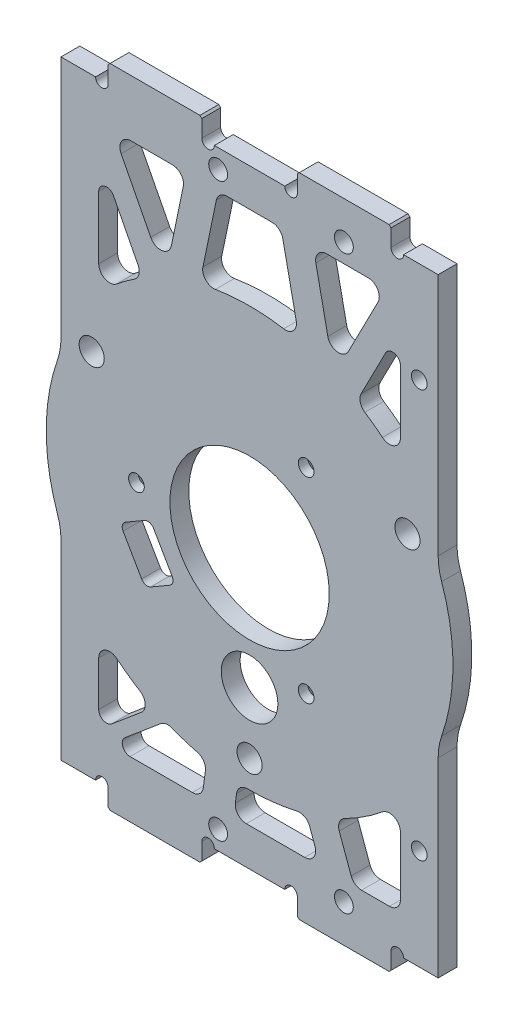
SolidWorks part; units mm, degrees
material "Thornel Mat VMA"
ref_plane "前视基准面" through (0, 0, 0) normal (0, 0, 1) x (1, 0, 0)
ref_plane "上视基准面" through (0, 0, 0) normal (0, 1, 0) x (1, 0, 0)
ref_plane "右视基准面" through (0, 0, 0) normal (1, 0, 0) x (0, 0, -1)
sketch "草图1" plane through (0, 0, 0) normal (0, 0, 1) x (1, 0, 0)
  line L1 (-30, 44.25) -> (30, 44.25)
  line L2 (-30, 44.25) -> (-30, -44.25)
  line L3 (-30, -44.25) -> (30, -44.25)
  line L4 (30, 44.25) -> (30, -44.25)
  line L5 (0, -44.25) -> (0, 44.25) construction
  line L6 (-30, 0) -> (30, 0) construction
  circle A0 centre (0, 0) radius 29 construction
  circle A1 centre (25.1147, 14.5) radius 2
  circle A2 centre (0, -29) radius 2
  circle A3 centre (-25.1147, 14.5) radius 2
  point P0 (0, 0)
  point P17 (0, 0)
  dimension "D1" = 58
  dimension "D4" = 4
  dimension "D3" = 44.25
  dimension "D2" = 60
  dimension "D5" = 3
extrude "凸台-拉伸1" add sketch "草图1" along normal blind 3
sketch "草图2" plane through (0, 0, 3) normal (0, 0, 1) x (1, 0, 0)
  circle A0 centre (0, 0) radius 12.675
  dimension "D1" = 25.35
extrude "切除-拉伸1" cut sketch "草图2" against normal blind 3
sketch "草图4" plane through (0, 0, 3) normal (0, 0, 1) x (1, 0, 0)
  line L0 (-12.7296, 10.3517) -> (-15.3296, 5.8483) construction
  line L1 (-12.7296, 10.3517) -> (-15.3296, 5.8483)
  line L2 (-16.0126, 5.6653) -> (-19.1303, 7.4653) construction
  line L3 (-16.0126, 5.6653) -> (-19.1303, 7.4653)
  line L4 (-19.3133, 8.1483) -> (-16.7133, 12.6517) construction
  line L5 (-19.3133, 8.1483) -> (-16.7133, 12.6517)
  circle A0 centre (-16.671, -9.625) radius 4 construction
  circle A1 centre (-16.671, -9.625) radius 4
sketch "草图5" plane through (0, 0, 3) normal (0, 0, 1) x (1, 0, 0)
  line L0 (-12.7296, 10.3517) -> (-15.3296, 5.8483) construction
  line L1 (-15.5796, 5.4153) -> (-12.0796, 11.4775)
  line L2 (-12.0796, 11.4775) -> (-16.0633, 13.7775)
  line L3 (-16.0633, 13.7775) -> (-19.5633, 7.7153)
  line L4 (-19.5633, 7.7153) -> (-15.5796, 5.4153)
  line L5 (-16.0126, 5.6653) -> (-19.1303, 7.4653) construction
  line L6 (-19.3133, 8.1483) -> (-16.7133, 12.6517) construction
  line L7 (-15.3966, 4.7323) -> (-11.3966, 11.6605)
  line L8 (-11.3966, 11.6605) -> (-16.2463, 14.4605)
  line L9 (-16.2463, 14.4605) -> (-20.2463, 7.5323)
  line L10 (-20.2463, 7.5323) -> (-15.3966, 4.7323)
  line L11 (12.4796, 10.7847) -> (15.9796, 4.7225)
  line L12 (15.9796, 4.7225) -> (19.9633, 7.0225)
  line L13 (19.9633, 7.0225) -> (16.4633, 13.0847)
  line L14 (16.4633, 13.0847) -> (12.4796, 10.7847)
  line L15 (11.7966, 10.9677) -> (15.7966, 4.0395)
  line L16 (15.7966, 4.0395) -> (20.6463, 6.8395)
  line L17 (20.6463, 6.8395) -> (16.6463, 13.7677)
  line L18 (16.6463, 13.7677) -> (11.7966, 10.9677)
  line L19 (3.1, -16.2) -> (-3.9, -16.2) construction
  line L20 (-3.9, -16.2) -> (-3.9, -20.8) construction
  line L21 (-3.9, -20.8) -> (3.1, -20.8) construction
  line L22 (3.1, -20.8) -> (3.1, -16.2) construction
  line L23 (3.6, -15.7) -> (-4.4, -15.7) construction
  line L24 (-4.4, -15.7) -> (-4.4, -21.3) construction
  line L25 (-4.4, -21.3) -> (3.6, -21.3) construction
  line L26 (3.6, -21.3) -> (3.6, -15.7) construction
  line L27 (-11.7966, -10.9677) -> (-15.7966, -4.0395)
  line L28 (-15.7966, -4.0395) -> (-20.6463, -6.8395)
  line L29 (-20.6463, -6.8395) -> (-16.6463, -13.7677)
  line L30 (-16.6463, -13.7677) -> (-11.7966, -10.9677)
  circle A0 centre (-16.671, -9.625) radius 4.5 construction
  circle A1 centre (0, 19.25) radius 4.5
  circle A2 centre (16.671, -9.625) radius 4.5
  circle A3 centre (0, -19.25) radius 4.5
  point P39 (0, 0)
  point P48 (0, 0)
  dimension "D1" = 9
  dimension "D2" = 7
  dimension "D3" = 0.5
  dimension "D6" = 60
  dimension "D4" = 3
  dimension "D5" = 2
extrude "切除-拉伸2" cut sketch "草图5" against normal blind 10 contours A0 | L29 L30 L27 L28 | A3 | L1 L2 L3 L4
sketch "草图6" plane through (0, 0, 3) normal (0, 0, 1) x (1, 0, 0)
  line L4 (30, -44.25) -> (30, 44.25)
  line L5 (30, 44.25) -> (-30, 44.25)
  line L6 (-30, 44.25) -> (-30, -44.25)
  line L7 (-30, -44.25) -> (30, -44.25)
  line L8 (30, -12.1046) -> (30, 12.1046)
  line L9 (30, 44.25) -> (-30, 44.25)
  line L10 (-30, 12.1046) -> (-30, -12.1046)
  arc A0 (-30, 12.1046) -> (-30, -12.1046) centre (0, 0) ccw
  arc A1 (30, -12.1046) -> (30, 12.1046) centre (0, 0) ccw
  line M10 (-30, 44.25) -> (-30, -44.25)
  dimension "D1" = 64.7
  dimension "D2" = 0
extrude "凸台-拉伸2" add sketch "草图6" against normal up to surface (3 mm away) contours A0 M10 | L8 A1 up to face at (-16.2215, -8.9036, 0)
sketch "草图7" plane through (0, 0, 0) normal (0, 0, -1) x (-1, 0, 0)
  line L0 (-30, 12.1046) -> (-30, 44.25) construction
  line L1 (30, 44.25) -> (-30, 44.25)
  line L2 (30, 44.25) -> (30, 52.65)
  line L3 (30, 52.65) -> (-30, 52.65)
  line L4 (-30, 44.25) -> (-30, 52.65)
  dimension "D1" = 8.4
extrude "凸台-拉伸3" add sketch "草图7" against normal up to surface (3 mm away) up to face at (-16.2215, -8.9036, 3)
sketch "草图8" plane through (0, 0, 0) normal (0, 0, -1) x (-1, 0, 0)
  line L0 (24, 12.1046) -> (24, 46.65)
  line L1 (24, 46.65) -> (-24, 46.65)
  line L2 (-24, 46.65) -> (-24, 12.1046)
  line L3 (-24, -12.1046) -> (-24, -38.25)
  line L4 (-24, -38.25) -> (24, -38.25)
  line L5 (24, -38.25) -> (24, -12.1046)
  line L6 (-30, -12.1046) -> (-30, -44.25)
  line L7 (-30, -44.25) -> (30, -44.25)
  line L8 (30, -44.25) -> (30, -12.1046)
  line L9 (30, 12.1046) -> (30, 52.65)
  line L10 (30, 52.65) -> (-30, 52.65)
  line L11 (-30, 52.65) -> (-30, 12.1046)
  line L12 (-30, -12.1046) -> (-30, -44.25)
  line L13 (-30, -44.25) -> (30, -44.25)
  line L14 (30, -44.25) -> (30, -12.1046)
  line L15 (30, 12.1046) -> (30, 52.65)
  line L16 (30, 52.65) -> (-30, 52.65)
  line L17 (-30, 52.65) -> (-30, 12.1046)
  line L18 (0, 0) -> (-13.9219, -38.25)
  line L19 (0, 0) -> (5.0357, -38.25)
  line L20 (1.1451, 10.4556) -> (11.5962, -68.9286)
  line L21 (1.1451, 10.4556) -> (-21.9953, -53.1222)
  line L22 (-1.1451, -10.4556) -> (5.3791, -60.0118)
  line L23 (-1.1451, -10.4556) -> (-15.2052, -49.0855)
  line L24 (1.1451, 10.4556) -> (-16.2711, -37.3949) construction
  line L25 (1.1451, 10.4556) -> (7.745, -39.6758) construction
  line L26 (0, 0) -> (0, -73.8949) construction
  line L27 (0, 0) -> (77.4058, 0) construction
  line L28 (24, 46.65) -> (15.6774, 30.4729) construction
  line L29 (-24, 46.65) -> (-15.4503, 30.0316) construction
  line L30 (-25.7784, 45.735) -> (-17.2288, 29.1167) construction
  line L31 (25.7784, 45.735) -> (17.4558, 29.558) construction
  line L32 (-1.1451, -10.4556) -> (-11.5726, -39.1051) construction
  line L33 (-1.1451, -10.4556) -> (2.7878, -40.3285) construction
  line L34 (21.8007, 46.747) -> (13.457, 30.5288)
  line L35 (-25.7784, 45.735) -> (-17.0078, 28.6872)
  line L36 (25.7784, 45.735) -> (17.0078, 28.6872)
  line L37 (-22.3053, 47.7277) -> (-13.457, 30.5288)
  line L38 (-22.2216, 47.565) -> (-13.6719, 30.9466) construction
  line L39 (22.2216, 47.565) -> (13.8989, 31.3879) construction
  line L40 (24, 46.65) -> (15.2569, 29.6555)
  line L41 (-8.0641, 46.65) -> (-11.2329, 31.4013) construction
  line L42 (-24, 46.65) -> (0, 0)
  line L43 (-10.1068, 46.65) -> (-13.457, 30.5288)
  line L44 (-5, 46.65) -> (-8.2957, 30.791)
  line L45 (-9.8954, 47.6673) -> (-13.1911, 31.8083) construction
  line L46 (-5, 46.65) -> (-8.2957, 30.791) construction
  line L47 (10.1068, 46.65) -> (13.457, 30.5288)
  line L48 (5, 46.65) -> (8.2957, 30.791)
  line L49 (-7.9372, 47.2604) -> (-11.2329, 31.4013) construction
  line L50 (0, 0) -> (5.2664, -40.0022) construction
  line L51 (14.3136, -30.1221) -> (24, -38.25) construction
  line L52 (13.3048, -30.5811) -> (23.3572, -39.016)
  line L53 (15.2918, -29.6375) -> (24.6428, -37.484)
  line L54 (9.1091, -27.0605) -> (23.3572, -39.016) construction
  line L55 (10.3947, -25.5284) -> (24.6428, -37.484) construction
  line L56 (9.7519, -26.2944) -> (24, -38.25) construction
  circle A0 centre (0, 0) radius 33.35
  arc A3 (30, -12.1046) -> (30, 12.1046) centre (0, 0) ccw
  arc A4 (-30, 12.1046) -> (-30, -12.1046) centre (0, 0) ccw
  dimension "D1" = 66.7
  dimension "D3" = 20
  dimension "D4" = 7.5
  dimension "D5" = 2.5
  dimension "D6" = 2.5
  dimension "D7" = 6
  dimension "D8" = 2
  dimension "D10" = 2
  dimension "D12" = 10
  dimension "D13" = 1
  dimension "D15" = 40
  dimension "D2" = 0
  dimension "D9" = 2
  dimension "D11" = 3
  dimension "D14" = 1
extrude "切除-拉伸3" cut sketch "草图8" against normal blind 10 contours A0 L35 L2 | L43 L1 L37 | A0 L48 L1 L44 | L1 L47 L34 | A0 L0 L36 | A0 L23 L4 L22 | A0 L3 L4 L21 | A0 L20 L4 L52 | A0 L53 L5
sketch "草图9" plane through (0, 0, 0) normal (0, 0, -1) x (-1, 0, 0)
  line L0 (5, 49.65) -> (-15, 49.65) construction
  line L1 (30, 52.65) -> (-30, 52.65) construction
  line L2 (0, 52.65) -> (0, -44.25) construction
  line L3 (-30, 12.1046) -> (-30, 52.65) construction
  line L4 (30, -44.25) -> (-30, -44.25) construction
  line L5 (0, 4.2) -> (43.367, 4.2) construction
  line L6 (-30, -44.25) -> (-30, -12.1046) construction
  circle A0 centre (5, 49.65) radius 1.5
  circle A1 centre (-15, 49.65) radius 1.5
  circle A2 centre (5, -41.25) radius 1.5
  circle A3 centre (-15, -41.25) radius 1.5
  circle A4 centre (-27, -28.25) radius 1.25
  circle A5 centre (-27, 36.65) radius 1.25
  dimension "D1" = 3
  dimension "D3" = 20
  dimension "D4" = 15
  dimension "D5" = 2.5
  dimension "D6" = 3
  dimension "D7" = 16
  dimension "D2" = 3
extrude "切除-拉伸4" cut sketch "草图9" against normal through all
fillet "圆角1" [suppressed] radius 1.5
sketch "草图10" plane through (0, 0, 0) normal (0, 0, -1) x (-1, 0, 0)
  line L0 (30, 52.65) -> (-30, 52.65) construction
  line L1 (-22.5, 55.65) -> (-7.6, 55.65)
  line L2 (-22.5, 55.65) -> (-22.5, 52.65)
  line L3 (-22.5, 52.65) -> (-7.6, 52.65)
  line L4 (-7.6, 55.65) -> (-7.6, 52.65)
  line L5 (0, 52.65) -> (0, -44.25) construction
  line L6 (30, -44.25) -> (-30, -44.25) construction
  line L7 (-30, 12.1046) -> (-30, 52.65) construction
  line L8 (22.5, 52.65) -> (7.6, 52.65)
  line L9 (7.6, 55.65) -> (7.6, 52.65)
  line L10 (22.5, 55.65) -> (7.6, 55.65)
  line L11 (22.5, 55.65) -> (22.5, 52.65)
  line L12 (0, 4.2) -> (63.6859, 4.2) construction
  line L13 (22.5, -47.25) -> (22.5, -44.25)
  line L14 (22.5, -47.25) -> (7.6, -47.25)
  line L15 (7.6, -47.25) -> (7.6, -44.25)
  line L16 (22.5, -44.25) -> (7.6, -44.25)
  line L17 (-22.5, -44.25) -> (-7.6, -44.25)
  line L18 (-7.6, -47.25) -> (-7.6, -44.25)
  line L19 (-22.5, -47.25) -> (-7.6, -47.25)
  line L20 (-22.5, -47.25) -> (-22.5, -44.25)
  dimension "D1" = 14.9
  dimension "D2" = 3
  dimension "D3" = 7.5
extrude "凸台-拉伸4" add sketch "草图10" against normal up to surface (3 mm away) up to face at (25.75, -28.25, 3)
sketch "草图11" plane through (0, 0, 0) normal (0, 0, -1) x (-1, 0, 0)
  line L0 (0, 52.65) -> (0, -44.25) construction
  line L1 (7.6, 52.65) -> (-7.6, 52.65) construction
  line L2 (7.6, -44.25) -> (-7.6, -44.25) construction
  line L3 (0, 4.2) -> (53.2603, 4.2) construction
  line L4 (-22.5, 52.65) -> (-30, 52.65) construction
  line L5 (-22.5, 55.65) -> (-22.5, 52.65) construction
  line L6 (-7.6, 52.65) -> (-7.6, 55.65) construction
  circle A0 centre (-23.5, 52.65) radius 1
  circle A1 centre (-6.6, 52.65) radius 1
  circle A2 centre (6.6, 52.65) radius 1
  circle A3 centre (23.5, 52.65) radius 1
  circle A4 centre (23.5, -44.25) radius 1
  circle A5 centre (6.6, -44.25) radius 1
  circle A6 centre (-6.6, -44.25) radius 1
  circle A7 centre (-23.5, -44.25) radius 1
  dimension "D1" = 2
extrude "切除-拉伸5" cut sketch "草图11" against normal through all
chamfer "倒角1" distance 0.3 angle 45 8 edges at (7.6, -47.25, 1.5) (22.5, -47.25, 1.5) (-22.5, -47.25, 1.5) (-7.6, -47.25, 1.5) (-22.5, 55.65, 1.5) (-7.6, 55.65, 1.5) (7.6, 55.65, 1.5) (22.5, 55.65, 1.5)
sketch "草图12" plane through (0, 0, 0) normal (0, 0, -1) x (-1, 0, 0)
  circle A0 centre (-9, 15.5885) radius 1.25
  circle A1 centre (18, 0) radius 1.25
  circle A2 centre (-9, -15.5885) radius 1.25
  point P8 (0, 0)
  dimension "D1" = 2.5
  dimension "D3" = 18
  dimension "D2" = 3
extrude "切除-拉伸6" cut sketch "草图12" against normal through all
sketch "草图13" plane through (0, 0, 0) normal (0, 0, -1) x (-1, 0, 0)
  line L0 (0, 0) -> (-30, 20.1046)
  line L1 (-30, 12.1046) -> (-30, 52.65) construction
  line L2 (30, 20.1046) -> (30, 12.1046)
  line L3 (-30, 20.1046) -> (-30, 12.1046)
  line L4 (30, 52.65) -> (30, 12.1046) construction
  line L5 (0, 0) -> (30, 20.1046)
  circle A0 centre (0, 0) radius 32.35
  arc A1 (-30, 12.1046) -> (-30, -12.1046) centre (0, 0) ccw construction
  dimension "D1" = 8
  dimension "D2" = 8
extrude "切除-拉伸7" [suppressed] cut sketch "草图13" against normal through all contours A0 L2 L5
fillet "圆角2" [suppressed] radius 1.5
fillet "圆角3" radius 10 2 edges at (-30, -12.1046, 1.5) (30, -12.1046, 1.5)
fillet "圆角4" radius 1.75 27 edges at (24, 23.1565, 1.5) (-24, 23.1565, 1.5) (11.2614, -38.25, 1.5) (-2.5141, -38.25, 1.5) (-1.8622, -33.298, 1.5) (-6.8194, -32.6453, 1.5) (-7.5573, -38.25, 1.5) (-24, -23.1565, 1.5) (9.025, -32.1056, 1.5) (16.5823, -38.25, 1.5) (24, -38.25, 1.5) (13.7235, -30.3955, 1.5) (24, -23.1565, 1.5) (5, 46.65, 1.5) (-5, 46.65, 1.5) (-7.9644, 32.385, 1.5) (7.9644, 32.385, 1.5) (17.0078, 28.6872, 1.5) (-17.0078, 28.6872, 1.5) (21.7508, 46.65, 1.5) (10.1068, 46.65, 1.5) (13.457, 30.5288, 1.5) (-13.457, 30.5288, 1.5) (-21.7508, 46.65, 1.5) (-10.1068, 46.65, 1.5) (-15.2918, -29.6375, 1.5) (-13.3048, -30.5811, 1.5)
fillet "圆角5" radius 1.05 4 edges at (-11.7966, -10.9677, 1.5) (-16.6463, -13.7677, 1.5) (-20.6463, -6.8395, 1.5) (-15.7966, -4.0395, 1.5)
fillet "圆角6" radius 1.25 4 edges at (-24, 42.2782, 1.5) (24, 42.2782, 1.5) (-24, -36.9446, 1.5) (-22.4443, -38.25, 1.5)
chamfer "倒角2" distance 1.5 angle 45 3 edges at (7.75, 15.5885, 0) (-19.25, 0, 0) (7.75, -15.5885, 0)
